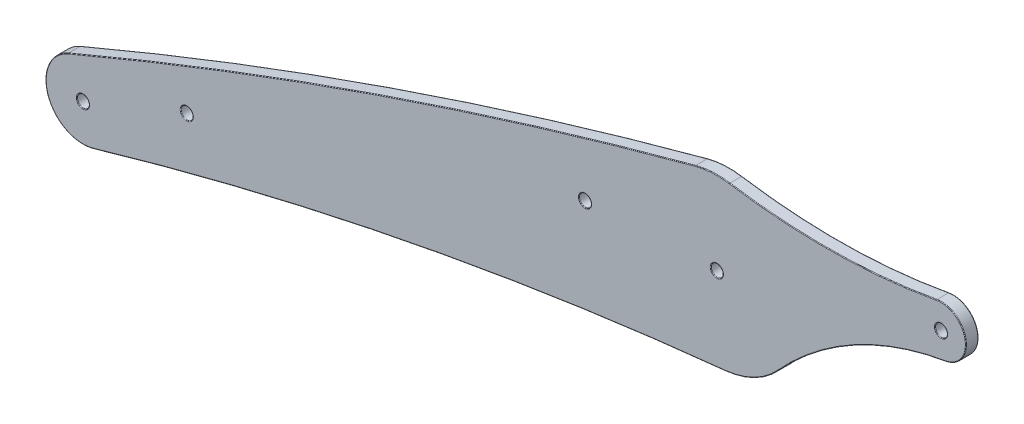
SolidWorks part; units mm, degrees
ref_plane "前视基准面" through (0, 0, 0) normal (0, 0, 1) x (1, 0, 0)
ref_plane "上视基准面" through (0, 0, 0) normal (0, 1, 0) x (1, 0, 0)
ref_plane "右视基准面" through (0, 0, 0) normal (1, 0, 0) x (0, 0, -1)
sketch "草图1" plane through (0, 0, 0) normal (0, 0, 1) x (1, 0, 0)
  line L0 (-219.8961, 156.8991) -> (-13.2252, 212.4253) construction
  line L1 (-219.8961, 156.8991) -> (-13.2252, 212.4253) construction
  circle A0 centre (-219.8961, 156.8991) radius 9 construction
  circle A1 centre (-13.2252, 212.4253) radius 6 construction
  circle A2 centre (-67.2252, 197.9171) radius 10 construction
  circle A3 centre (-67.2252, 197.9171) radius 20 construction
  arc A4 (-223.4128, 165.1836) -> (-72.4141, 217.2323) centre (225.9437, -893.3903) cw
  arc A5 (-217.3703, 148.2608) -> (-65.193, 178.0206) centre (21.1745, -667.5801) cw
  arc A6 (-64.1576, 217.6805) -> (-14.2993, 218.3284) centre (-41.1504, 365.9055) ccw
  arc A7 (-52.4027, 184.4898) -> (-12.2225, 206.5097) centre (-0.5239, 137.4941) cw
  arc A8 (-72.4141, 217.2323) -> (-64.1576, 217.6805) centre (-67.2252, 197.9171) cw
  arc A9 (-65.193, 178.0206) -> (-52.4027, 184.4898) centre (-67.2252, 197.9171) ccw
  arc A10 (-14.2993, 218.3284) -> (-12.2225, 206.5097) centre (-13.2252, 212.4253) cw
  arc A11 (-223.4128, 165.1836) -> (-217.3703, 148.2608) centre (-219.8961, 156.8991) ccw
  arc A12 (-219.8961, 156.8991) -> (-13.2252, 212.4253) centre (86.5304, -571.2512) cw construction
  point P2 (-67.2252, 197.9171)
  point P26 (-194.8961, 166.9217)
  point P27 (-98.9752, 196.6601)
  dimension "D1" = 18
  dimension "D2" = 40
  dimension "D3" = 20
  dimension "D4" = 12
  dimension "D5" = 850
  dimension "D6" = 1150
  dimension "D7" = 70
  dimension "D8" = 150
  dimension "D9" = 790
  dimension "D10" = 31.75
  dimension "D11" = 25
extrude "凸台-拉伸1" add sketch "草图1" against normal blind 3
hole_wizard "M3.5 螺纹孔的螺纹孔钻头1" positions "草图2" profile "草图3" hole size "M3.5" standard "ISO" end condition through all
sketch "草图2" plane through (0, 0, 0) normal (0, 0, 1) x (1, 0, 0)
  point P0 (-219.8961, 156.8991)
  point P3 (-194.8961, 166.9217)
  point P6 (-98.9752, 196.6601)
  point P9 (-67.2252, 197.9171)
  point P12 (-13.2252, 212.4253)
sketch "草图3" plane through (-219.8961, 156.8991, 0) normal (1, 0, 0) x (0, -1, 0)
  line L0 (0, 0) -> (0, 3)
  line L1 (0, 3) -> (1.45, 3)
  line L2 (1.45, 3) -> (1.45, 0)
  line L5 (1.45, 0) -> (0, 0)
  line L11 (0, -6.35) -> (0, 107.95) construction
  dimension "通孔孔直径" = 2.9
  dimension "通孔孔深度" = 3
fillet "圆角1" radius 0.15 26 edges at (-141.9617, 166.618, -3) (-58.1985, 180.0701, -3) (-34.1653, 198.8803, -3) (-7.3158, 213.4637, -3) (-39.2013, 215.9182, -3) (-68.3092, 217.8877, -3) (-148.8181, 193.8325, -3) (-228.372, 153.8727, -3) (-11.7752, 212.4253, -3) (-65.7752, 197.9171, -3) (-97.5252, 196.6601, -3) (-193.4461, 166.9217, -3) (-218.4461, 156.8991, -3) (-148.8181, 193.8325, 0) (-68.3092, 217.8877, 0) (-39.2013, 215.9182, 0) (-7.3158, 213.4637, 0) (-34.1653, 198.8803, 0) (-58.1985, 180.0701, 0) (-141.9617, 166.618, 0) (-228.372, 153.8727, 0) (-11.7752, 212.4253, 0) (-65.7752, 197.9171, 0) (-97.5252, 196.6601, 0) (-193.4461, 166.9217, 0) (-218.4461, 156.8991, 0)
